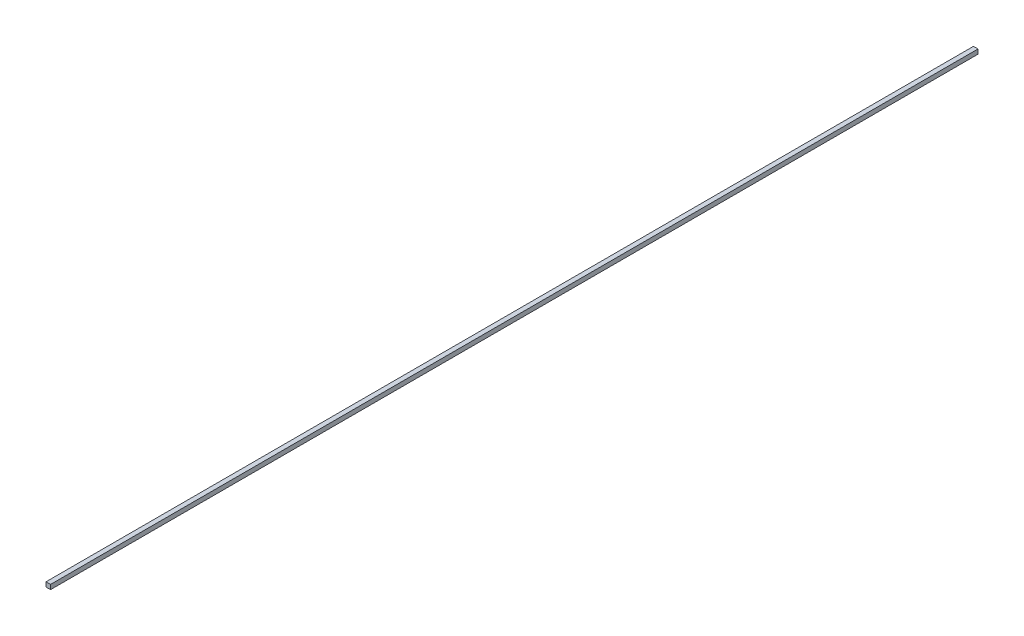
SolidWorks part; units mm, degrees
material "Balsa"
ref_plane "Front Plane" through (0, 0, 0) normal (0, 0, 1) x (1, 0, 0)
ref_plane "Top Plane" through (0, 0, 0) normal (0, 1, 0) x (1, 0, 0)
ref_plane "Right Plane" through (0, 0, 0) normal (1, 0, 0) x (0, 0, -1)
sketch "Sketch1" plane through (0, 0, 0) normal (0, 0, 1) x (1, 0, 0)
  line L0 (0, 0) -> (0, 13.8818) construction
  line L1 (0, 0) -> (9.7636, 0) construction
  line L2 (9.7636, 0) -> (-12.6545, 0) construction
  line L3 (-4.5, -4.5) -> (-4.5, 4.5)
  line L4 (-4.5, 4.5) -> (4.5, 4.5)
  line L5 (4.5, -4.5) -> (4.5, 4.5)
  line L6 (-4.5, -4.5) -> (4.5, -4.5)
  point P9 (0, 4.5)
  point P11 (4.5, 0)
  point P12 (-4.5, 0)
  dimension "D1" = 4.5
  dimension "D2" = 4.5
extrude "Boss-Extrude1" add sketch "Sketch1" along normal blind 916.874
mirror "Mirror1" about plane through (0, 0, 0) normal (0, 0, 1) of bodies 101
